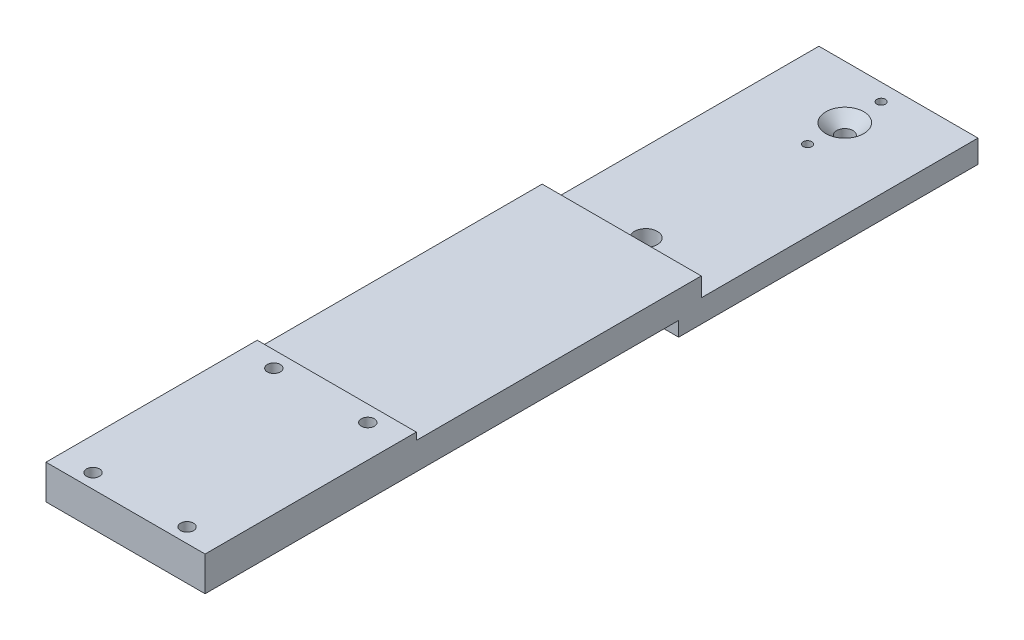
SolidWorks part; units mm, degrees
material "6061 Alloy"
ref_plane "Front" through (0, 0, 0) normal (0, 0, 1) x (1, 0, 0)
ref_plane "Top" through (0, 0, 0) normal (0, 1, 0) x (1, 0, 0)
ref_plane "Right" through (0, 0, 0) normal (1, 0, 0) x (0, 0, -1)
sketch "Sketch1" plane through (0, 0, 0) normal (0, 1, 0) x (1, 0, 0)
  line L0 (0, 81.474) -> (0, -81.474) construction
  line L1 (-22, 81.474) -> (22, 81.474)
  line L2 (-22, 81.474) -> (-22, -81.474)
  line L3 (-22, -81.474) -> (22, -81.474)
  line L4 (22, 81.474) -> (22, -81.474)
  dimension "D1" = 44
  dimension "D2" = 162.948
extrude "Extrude1" add sketch "Sketch1" along normal blind 9.525
sketch "Sketch5" plane through (0, 9.525, 0) normal (0, 1, 0) x (1, 0, 0)
  line L0 (22, -81.474) -> (22, 81.474) construction
  line L1 (-22, 81.474) -> (22, 81.474)
  line L2 (-22, 81.474) -> (-22, -23.054)
  line L3 (-22, -23.054) -> (22, -23.054)
  line L4 (22, 81.474) -> (22, -23.054)
  line L5 (-22, -81.474) -> (22, -81.474) construction
  dimension "D1" = 58.42
extrude "Extrude3" cut sketch "Sketch5" against normal blind 2
sketch "Sketch7" plane through (0, 7.525, 0) normal (0, 1, 0) x (1, 0, 0)
  line L0 (-22, 81.474) -> (-22, -23.054) construction
  line L1 (22, 81.474) -> (-22, 81.474)
  line L2 (22, 81.474) -> (22, 55.7388)
  line L3 (22, 55.7388) -> (-22, 55.7388)
  line L4 (-22, 81.474) -> (-22, 55.7388)
extrude "Extrude5" cut sketch "Sketch7" against normal blind 5.25
sketch "Sketch6" plane through (0, 0, 0) normal (0, -1, 0) x (1, 0, 0)
  line L0 (22, 81.474) -> (22, -81.474) construction
  line L1 (-22, -81.474) -> (22, -81.474)
  line L2 (-22, -81.474) -> (-22, -49.4877)
  line L3 (-22, -49.4877) -> (22, -49.4877)
  line L4 (22, -81.474) -> (22, -49.4877)
extrude "Extrude4" add sketch "Sketch6" along normal blind 4.032
hole_wizard "1/4 (0.25) Diameter Hole1" positions "Sketch4" profile "Sketch3" hole size "1/4" standard "Ansi Inch"
sketch "Sketch4" plane through (-11.9094, -4.032, 7.9942) normal (0, -1, 0) x (1, 0, 0)
  circle A1 centre (11.9094, -70.4182) radius 2.5527 construction
  point P0 (11.9094, -70.4182)
sketch "Sketch3" plane through (0, -4.032, -62.424) normal (1, 0, 0) x (0, 0, -1)
  line L0 (0, 0) -> (0, 18.618)
  line L1 (0, 18.618) -> (3.175, 18.618)
  line L2 (3.175, 18.618) -> (3.175, 0)
  line L5 (3.175, 0) -> (0, 0)
  line L10 (0, 18.618) -> (-3.175, 18.618) construction
  line L11 (0, -6.35) -> (0, 107.95) construction
  dimension "Hole Dia." = 6.35
  dimension "Hole Depth" = 18.618
  dimension "Drill Angle" = 180
sketch "Sketch8" plane through (0, 0, -81.474) normal (0, 0, -1) x (-1, 0, 0)
  line L1 (22, 2.275) -> (-22, 2.275)
  line L2 (22, 2.275) -> (22, -4.032)
  line L3 (22, -4.032) -> (-22, -4.032)
  line L4 (-22, 2.275) -> (-22, -4.032)
extrude "Extrude6" add sketch "Sketch8" along normal blind 50.8
hole_wizard "CBORE for M3 SBHCS1" positions "Sketch10" profile "Sketch9" counterbore size "M3" standard "Ansi Metric" end condition through all
sketch "Sketch10" plane through (0, 0, 0) normal (0, -1, 0) x (1, 0, 0)
  circle A0 centre (-13, 77.474) radius 1.5 construction
  circle A1 centre (13, 77.474) radius 1.5 construction
  circle A2 centre (-13, 27.474) radius 1.5 construction
  circle A3 centre (13, 27.474) radius 1.5 construction
  point P0 (-13, 77.474)
  point P1 (13, 77.474)
  point P3 (13, 27.474)
  point P5 (-13, 27.474)
sketch "Sketch9" plane through (-13, 0, 77.474) normal (1, 0, 0) x (0, 0, -1)
  line L0 (0, 0) -> (0, 9.525)
  line L1 (0, 9.525) -> (1.8, 9.525)
  line L3 (1.8, 9.525) -> (1.8, 1.65)
  line L4 (1.8, 1.65) -> (3.35, 1.65)
  line L5 (3.35, 1.65) -> (3.35, 0)
  line L7 (3.35, 0) -> (0, 0)
  line L11 (0, -6.35) -> (0, 107.95) construction
  dimension "Thru Hole Dia." = 3.6
  dimension "Thru Hole Depth" = 9.525
  dimension "C'Bore Dia." = 6.7
  dimension "C'Bore Depth" = 1.65
sketch "Sketch12" plane through (0, 2.275, 0) normal (0, 1, 0) x (-1, 0, 0)
  circle A0 centre (0.1001, -127.575) radius 1.1906
  circle A1 centre (0.1001, -107.255) radius 1.1906
  dimension "D1" = 2.3813
extrude "Cut-Extrude1" cut sketch "Sketch12" against normal through all
hole_wizard "M4 Clearance Hole1" positions "Sketch14" profile "Sketch13" hole size "M4" standard "Ansi Metric"
sketch "Sketch14" plane through (0, 2.275, 0) normal (0, 1, 0) x (-1, 0, 0)
  line L0 (0.1001, -127.575) -> (0.1001, -107.5055) construction
  point P0 (0.1001, -117.5403)
sketch "Sketch13" plane through (-0.1001, 2.275, -117.5403) normal (1, 0, 0) x (0, 0, 1)
  line L0 (0, 0) -> (0, 8.204)
  line L1 (0, 8.204) -> (2.25, 8.204)
  line L2 (2.25, 8.204) -> (2.25, 0)
  line L5 (2.25, 0) -> (0, 0)
  line L10 (0, 8.204) -> (-2.25, 8.204) construction
  line L11 (0, -6.35) -> (0, 107.95) construction
  dimension "Hole Dia." = 4.5
  dimension "Hole Depth" = 8.204
  dimension "Drill Angle" = 180
chamfer "Chamfer1" distance 3 angle 45 1 edges at (-0.1001, 2.275, -115.2903)
